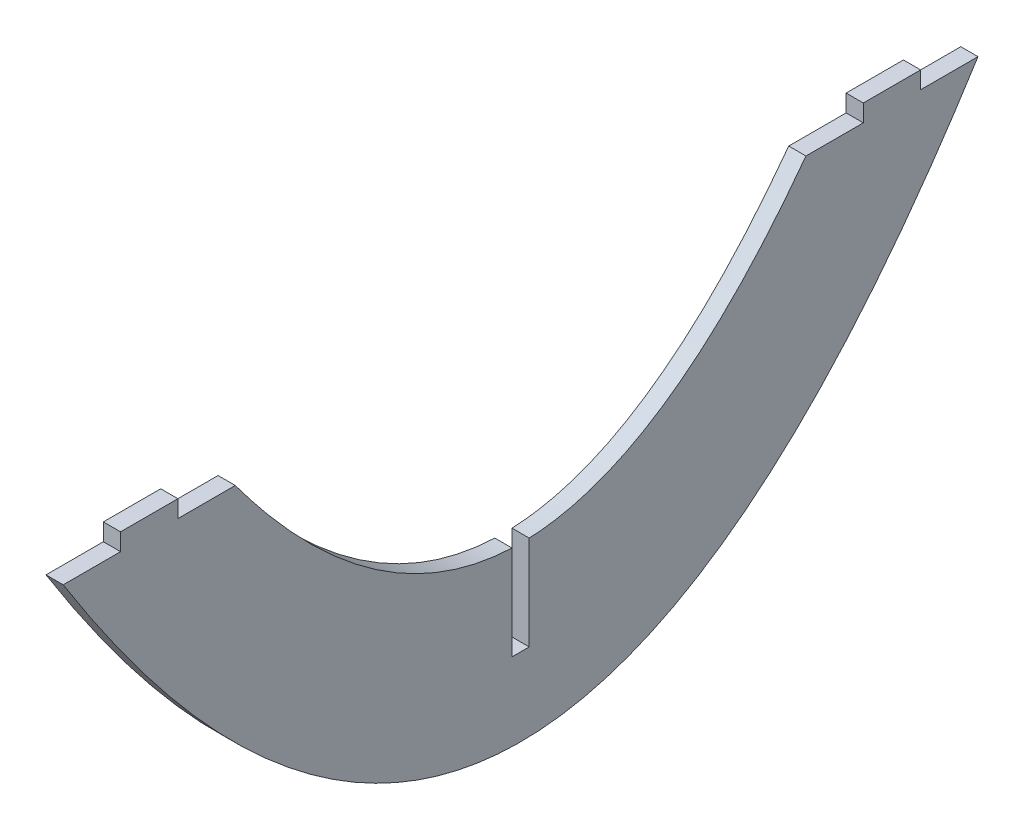
SolidWorks part; units mm, degrees
ref_plane "前视基准面" through (0, 0, 0) normal (0, 0, 1) x (1, 0, 0)
ref_plane "上视基准面" through (0, 0, 0) normal (0, 1, 0) x (1, 0, 0)
ref_plane "右视基准面" through (0, 0, 0) normal (1, 0, 0) x (0, 0, -1)
sketch "草图1" plane through (0, 0, 0) normal (1, 0, 0) x (0, 0, -1)
  line L0 (-79.7507, 150.0005) -> (-49.7511, 150.0005)
  line L1 (49.7511, 150.0005) -> (79.7507, 150.0005)
  spline S0 degree 2 poles (-90.5332, 168.3613) (0, 4.4362) (90.5332, 168.3613) knots 0 0 0 1 1 1 construction
  spline S1 degree 2 poles (-79.7507, 150.0005) (0, 22.797) (79.7507, 150.0005) knots 0.05955 0.05955 0.05955 0.94045 0.94045 0.94045
  spline S2 degree 2 poles (-89.5889, 225.3582) (0, 7.4393) (89.5889, 225.3582) knots 0 0 0 1 1 1 construction
  spline S3 degree 2 poles (-49.7511, 150.0005) (0, 82.797) (49.7511, 150.0005) knots 0.222337 0.222337 0.222337 0.777663 0.777663 0.777663
extrude "凸台-拉伸1" add sketch "草图1" along normal blind 3
sketch "草图2" plane through (0, 150.0005, 0) normal (0, 1, 0) x (1, 0, 0)
  line L0 (0, 79.7507) -> (3, 49.7511)
  line L1 (0, -49.7511) -> (3, -79.7507)
  line L2 (3, -49.7511) -> (3, -79.7507) construction
  line L3 (0, -69.7509) -> (3, -69.7509)
  line L4 (0, -69.7509) -> (0, -59.7509)
  line L5 (0, -59.7509) -> (3, -59.7509)
  line L6 (3, -69.7509) -> (3, -59.7509)
  line L7 (0, -69.7509) -> (3, -59.7509) construction
  line L8 (0, -59.7509) -> (3, -69.7509) construction
  line L9 (3, 79.7507) -> (3, 49.7511) construction
  line L10 (0, 59.7509) -> (3, 59.7509)
  line L11 (0, 59.7509) -> (0, 69.7509)
  line L12 (0, 69.7509) -> (3, 69.7509)
  line L13 (3, 59.7509) -> (3, 69.7509)
  line L14 (0, 59.7509) -> (3, 69.7509) construction
  line L15 (0, 69.7509) -> (3, 59.7509) construction
  point P8 (1.5, -64.7509)
  point P15 (1.5, 64.7509)
  line M2 (0, -49.7511) -> (0, -79.7507)
  line M4 (3, -79.7507) -> (3, -49.7511)
extrude "凸台-拉伸2" add sketch "草图2" along normal blind 3 contours L5 L1 L3 M4 | L5 L3 L1 M2 | L12 L11 L10 L0 | L10 L13 L12 L0
sketch "草图3" plane through (0, 0, 0) normal (-1, 0, 0) x (0, 0, 1)
  line L0 (-1.5, 99.9904) -> (-1.5, 88.5719) construction
  line L1 (-1.5, 99.9904) -> (-1.5, 88.5719)
  line L2 (1.5, 99.9904) -> (1.5, 88.5719) construction
  line L3 (1.5, 99.9904) -> (1.5, 88.5719)
  line L5 (-1.5, 99.9904) -> (1.5, 99.9904)
  line L6 (-1.5, 99.9904) -> (-1.5, 121.8715)
  line L7 (-1.5, 121.8715) -> (1.5, 121.8715)
  line L8 (1.5, 99.9904) -> (1.5, 121.8715)
  spline M1 degree 2 poles (49.7511, 150.0005) (0, 82.797) (-49.7511, 150.0005) knots 0.222337 0.222337 0.222337 0.777663 0.777663 0.777663
extrude "切除-拉伸1" cut sketch "草图3" against normal through all contours L5 L8 L6 M1
